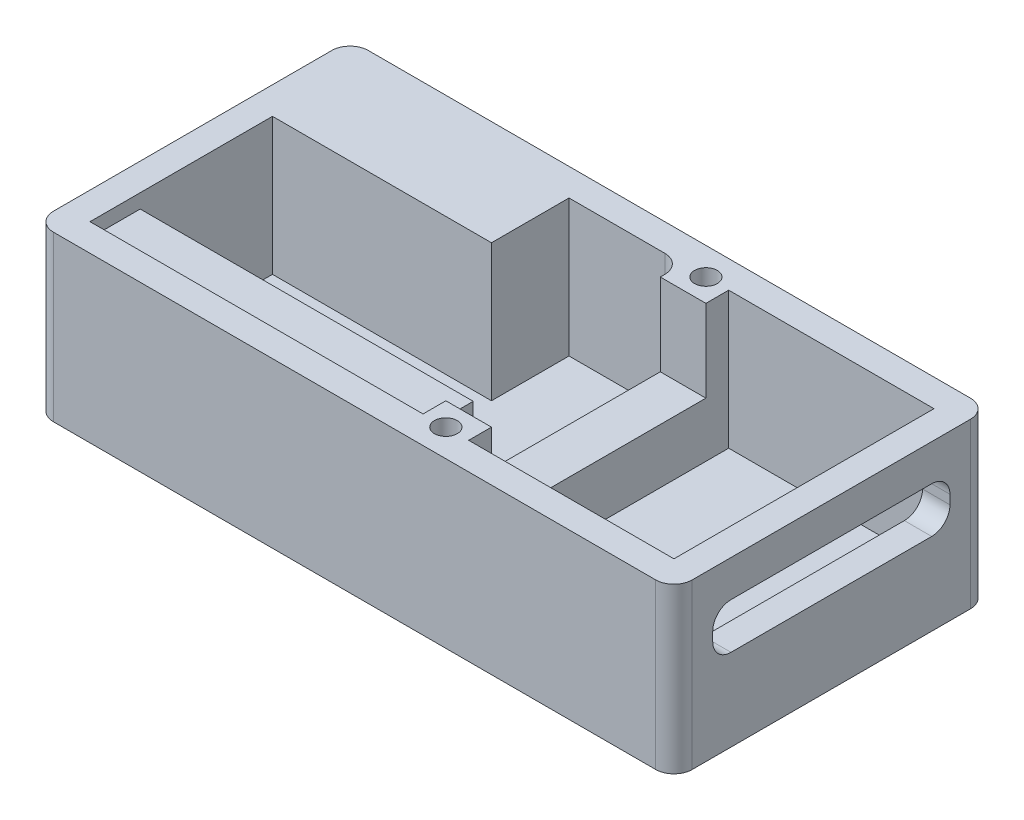
SolidWorks part; units mm, degrees
ref_plane "Front" through (0, 0, 0) normal (0, 0, 1) x (1, 0, 0)
ref_plane "Top" through (0, 0, 0) normal (0, 1, 0) x (1, 0, 0)
ref_plane "Right" through (0, 0, 0) normal (1, 0, 0) x (0, 0, -1)
sketch "Sketch1" plane through (0, 0, 0) normal (0, 1, 0) x (1, 0, 0)
  line L1 (-35, -17.25) -> (35, -17.25)
  line L2 (-35, -17.25) -> (-35, 17.25)
  line L3 (-35, 17.25) -> (35, 17.25)
  line L4 (35, -17.25) -> (35, 17.25)
  line L5 (-35, -17.25) -> (35, 17.25) construction
  line L6 (-35, 17.25) -> (35, -17.25) construction
  point P0 (0, 0)
  dimension "D1" = 70
  dimension "D2" = 34.5
extrude "Boss-Extrude1" add sketch "Sketch1" along normal blind 3
sketch "Sketch2" plane through (0, 3, 0) normal (0, 1, 0) x (1, 0, 0)
  line L4 (35, -17.25) -> (35, 17.25)
  line L5 (35, 17.25) -> (-35, 17.25)
  line L6 (-35, 17.25) -> (-35, -17.25)
  line L7 (-35, -17.25) -> (35, -17.25)
  line L8 (35, -17.25) -> (35, 17.25)
  line L9 (35, 17.25) -> (-35, 17.25)
  line L10 (-35, 17.25) -> (-35, -17.25)
  line L11 (-35, -17.25) -> (35, -17.25)
  dimension "D1" = 0
extrude "Extrude-Thin1" add sketch "Sketch2" along normal blind 15 thin thin type one direction reverse wall 3
sketch "Sketch3" plane through (35, 0, 0) normal (1, 0, 0) x (0, 0, -1)
  line L1 (-13, 9) -> (13, 9)
  line L2 (-13, 9) -> (-13, 14)
  line L3 (-13, 14) -> (13, 14)
  line L4 (13, 9) -> (13, 14)
  line L5 (-17.25, 0) -> (17.25, 0) construction
  point P4 (0, 9)
  dimension "D1" = 5
  dimension "D2" = 26
  dimension "D3" = 9
extrude "Cut-Extrude1" cut sketch "Sketch3" against normal up to next
sketch "Sketch4" [suppressed] plane through (0, 4, 0) normal (0, 1, 0) x (1, 0, 0)
  line L1 (11.75, 14.25) -> (30.25, 14.25)
  line L2 (11.75, 14.25) -> (11.75, -14.25)
  line L3 (11.75, -14.25) -> (30.25, -14.25)
  line L4 (30.25, 14.25) -> (30.25, -14.25)
  line L5 (35, -17.25) -> (35, 17.25) construction
  point P4 (11.75, 0)
  point P5 (21, 14.25)
  dimension "D1" = 18.5
  dimension "D2" = 28.5
  dimension "D3" = 14
extrude "Cut-Extrude2" [suppressed] cut sketch "Sketch4" against normal through all
chamfer "Chamfer1" [suppressed] distance 1.5 angle 70
sketch "Sketch5" [suppressed] plane through (0, 4, 0) normal (0, 1, 0) x (1, 0, 0)
  line L0 (-35, 17.25) -> (-35, -17.25) construction
  line L1 (-30, 11.5) -> (3, 11.5)
  line L2 (-30, 11.5) -> (-30, -11.5)
  line L3 (-30, -11.5) -> (3, -11.5)
  line L4 (3, 11.5) -> (3, -11.5)
  point P4 (3, 0)
  dimension "D1" = 23
  dimension "D2" = 5
  dimension "D3" = 33
extrude "Cut-Extrude3" [suppressed] cut sketch "Sketch5" against normal through all
sketch "Sketch6" plane through (0, 3, 0) normal (0, 1, 0) x (1, 0, 0)
  line L1 (32, 14.25) -> (-32, 14.25) construction
  line L2 (4.5, 14.25) -> (4.5, -14.25)
  line L7 (9.5, -14.25) -> (9.5, 14.25)
  line L11 (32, -14.25) -> (32, 14.25) construction
  line L12 (32, 14.25) -> (-32, 14.25) construction
  line L13 (-32, -14.25) -> (32, -14.25) construction
  line L16 (4.5, 14.25) -> (9.5, 14.25)
  line L17 (4.5, -14.25) -> (9.5, -14.25)
  dimension "D2" = 22.5
  dimension "D3" = 5
extrude "Boss-Extrude2" add sketch "Sketch6" along normal up to surface (15 mm away) up to face at (0, 18, 0)
sketch "Sketch7" plane through (0, 3, 0) normal (0, 1, 0) x (1, 0, 0)
  line L1 (-32, 14.25) -> (-8, 14.25)
  line L2 (-32, 14.25) -> (-32, 5.75)
  line L3 (-32, 5.75) -> (-8, 5.75)
  line L4 (-8, 14.25) -> (-8, 5.75)
  dimension "D1" = 8.5
  dimension "D2" = 24
extrude "Boss-Extrude3" add sketch "Sketch7" along normal up to surface (15 mm away) up to face at (20.75, 18, 0)
sketch "Sketch8" plane through (0, 3, 0) normal (0, 1, 0) x (1, 0, 0)
  line L0 (4.5, 14.25) -> (4.5, -14.25) construction
  line L1 (-32, -14.25) -> (4.5, -14.25)
  line L2 (-32, -14.25) -> (-32, -8.75)
  line L3 (-32, -8.75) -> (4.5, -8.75)
  line L4 (4.5, -14.25) -> (4.5, -8.75)
  dimension "D1" = 5.5
extrude "Boss-Extrude4" add sketch "Sketch8" along normal offset from surface (13.45 mm away) 1.55 up to face at (20.75, 18, 0)
sketch "Sketch9" [suppressed] plane through (0, 0, 0) normal (0, -1, 0) x (1, 0, 0)
  line L0 (-35, -17.25) -> (-35, 17.25) construction
  line L1 (-32.5, 12) -> (3.5, 12)
  line L2 (-32.5, 12) -> (-32.5, -12)
  line L3 (-32.5, -12) -> (3.5, -12)
  line L4 (3.5, 12) -> (3.5, -12)
  line L5 (-30, 11.5) -> (3, 11.5) construction
  point P4 (3.5, 0)
  dimension "D1" = 2.5
  dimension "D2" = 36
  dimension "D3" = 0.5
extrude "Cut-Extrude4" [suppressed] cut sketch "Sketch9" against normal blind 1.6
sketch "Sketch10" [suppressed] plane through (0, 4, 0) normal (0, 1, 0) x (1, 0, 0)
  line L0 (3, 11.5) -> (-30, 11.5) construction
  line L1 (3, -11.5) -> (-20, -11.5)
  line L2 (3, -11.5) -> (3, -10.2)
  line L3 (3, -10.2) -> (-4.667, -10.2)
  line L4 (-20, -11.5) -> (-20, -10.2)
  line L5 (-26, 11.5) -> (-7.5, 11.5)
  line L6 (-26, 11.5) -> (-26, 9.2)
  line L7 (-26, 9.2) -> (-7.5, 9.2)
  line L8 (-7.5, 11.5) -> (-7.5, 9.2)
  line L9 (-30, 11.5) -> (-30, -11.5) construction
  line L10 (3, -11.5) -> (3, 11.5) construction
  line L11 (-30, -11.5) -> (-28.8, -11.5)
  line L12 (-30, -11.5) -> (-30, 6.5)
  line L13 (-30, 6.5) -> (-28.8, 6.5)
  line L14 (-28.8, -11.5) -> (-28.8, 6.5)
  line L15 (3, 8.5) -> (0, 8.5)
  line L16 (3, 8.5) -> (3, 2.5)
  line L17 (3, 2.5) -> (0, 2.5)
  line L18 (0, 8.5) -> (0, 2.5)
  line L19 (-8.333, -10.2) -> (-20, -10.2)
  arc A0 (-8.333, -10.2) -> (-4.667, -10.2) centre (-6.5, -9.4) ccw
  dimension "D11" = 13.5
  dimension "D12" = 2
  dimension "D13" = 0.1
  dimension "D1" = 18.5
  dimension "D2" = 4
  dimension "D3" = 2.3
  dimension "D4" = 1.3
  dimension "D5" = 10
  dimension "D6" = 18
  dimension "D7" = 1.2
  dimension "D8" = 3
  dimension "D9" = 6
  dimension "D10" = 3
extrude "Boss-Extrude5" [suppressed] add sketch "Sketch10" against normal up to surface (2.4 mm away)
fillet "Fillet1" radius 2 4 edges at (33.5, 9, 13) (33.5, 14, 13) (33.5, 14, -13) (33.5, 9, -13)
fillet "Fillet2" radius 2 4 edges at (35, 9, -17.25) (-35, 9, -17.25) (-35, 9, 17.25) (35, 9, 17.25)
fillet "Fillet3" [suppressed] radius 1
sketch "Sketch11" [suppressed] plane through (0, 4, 0) normal (0, 1, 0) x (1, 0, 0)
  line L0 (3, 0) -> (11.7059, 0) construction
  line L3 (11.7059, -14.25) -> (11.7059, 14.25) construction
  line L4 (3, -9.2) -> (3, 1.5) construction
  circle A0 centre (6.9959, 14.25) radius 1.75
  circle A1 centre (6.9959, -14.25) radius 1.75
  dimension "D1" = 3.5
  dimension "D2" = 28.5
  dimension "D3" = 4.71
extrude "Cut-Extrude5" [suppressed] cut sketch "Sketch11" against normal through all
sketch "Sketch12" plane through (0, 18, 0) normal (0, 1, 0) x (1, 0, 0)
  line L0 (4.5, 14.25) -> (4.5, -14.25) construction
  line L1 (4.5, 11.75) -> (9.5, 11.75)
  line L2 (4.5, 11.75) -> (4.5, -11.75)
  line L3 (4.5, -11.75) -> (9.5, -11.75)
  line L4 (9.5, 11.75) -> (9.5, -11.75)
  line L5 (9.5, -14.25) -> (9.5, 14.25) construction
  line L6 (33, 17.25) -> (-33, 17.25) construction
  point P10 (4.5, 0)
  dimension "D1" = 5.5
extrude "Cut-Extrude6" cut sketch "Sketch12" against normal up to surface (9 mm away) up to face at (33.5, 9, 0)
sketch "Sketch13" plane through (0, 18, 0) normal (0, 1, 0) x (1, 0, 0)
  line L0 (0, 0) -> (9.5, 0) construction
  line L1 (9.5, -14.25) -> (9.5, 14.25) construction
  line L3 (9.5, 11.75) -> (4.5, 11.75) construction
  circle A0 centre (7, 14.25) radius 1.25
  circle A1 centre (7, -14.25) radius 1.25
  point P13 (7, 11.75)
  dimension "D1" = 28.5
  dimension "D2" = 2.5
extrude "Cut-Extrude7" cut sketch "Sketch13" against normal blind 10
fillet "Fillet4" radius 2 1 edges at (4.5, 10.5, -14.25)
